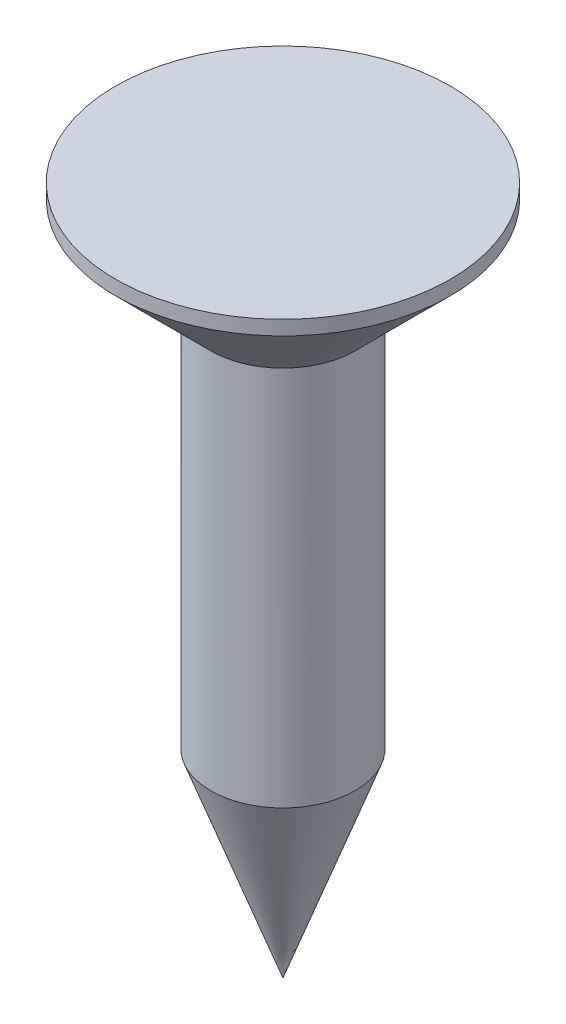
SolidWorks part; units mm, degrees
ref_plane "Front Plane" through (0, 0, 0) normal (0, 0, 1) x (1, 0, 0)
ref_plane "Top Plane" through (0, 0, 0) normal (0, 1, 0) x (1, 0, 0)
ref_plane "Right Plane" through (0, 0, 0) normal (1, 0, 0) x (0, 0, -1)
sketch "Sketch1" plane through (0, 0, 0) normal (0, 0, 1) x (1, 0, 0)
  line L0 (0, 4.25) -> (-2.9, 4.25)
  line L1 (-1.25, -4.25) -> (1.25, -4.25) construction
  line L2 (-1.25, -4.25) -> (-1.25, 4.25) construction
  line L3 (-1.25, 4.25) -> (1.25, 4.25) construction
  line L4 (1.25, -4.25) -> (1.25, 4.25) construction
  line L5 (-1.25, -4.25) -> (1.25, 4.25) construction
  line L6 (-1.25, 4.25) -> (1.25, -4.25) construction
  line L7 (-2.9, 4.25) -> (-2.9, 4)
  line L8 (-2.9, 4) -> (-1.25, 2.35)
  line L9 (-1.25, 2.35) -> (-1.25, -4.25)
  line L10 (-1.25, -4.25) -> (0, -7.6843)
  line L11 (0, -7.6843) -> (0, 4.25)
  point P0 (0, 0)
  dimension "D1" = 2.5
  dimension "D2" = 8.5
  dimension "D3" = 45
  dimension "D4" = 2.9
  dimension "D5" = 0.25
  dimension "D6" = 20
revolve "Revolve1" add sketch "Sketch1" angle 360 about L11
